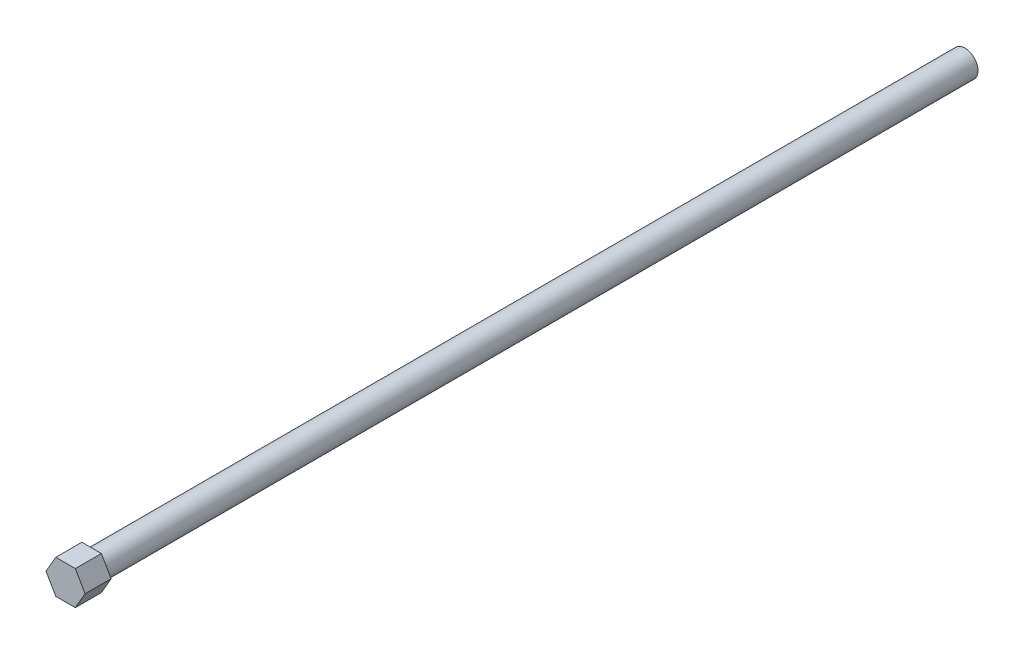
SolidWorks part; units mm, degrees
ref_plane "前视基准面" through (0, 0, 0) normal (0, 0, 1) x (1, 0, 0)
ref_plane "上视基准面" through (0, 0, 0) normal (0, 1, 0) x (1, 0, 0)
ref_plane "右视基准面" through (0, 0, 0) normal (1, 0, 0) x (0, 0, -1)
sketch "草图1" plane through (0, 0, 0) normal (0, 0, 1) x (1, 0, 0)
  circle A0 centre (0, 0) radius 5
  dimension "D1" = 10
extrude "凸台-拉伸1" add sketch "草图1" along normal blind 280
sketch "草图2" plane through (0, 0, 280) normal (0, 0, 1) x (1, 0, 0)
  line L1 (3.75, -6.4952) -> (7.5, 0)
  line L2 (7.5, 0) -> (3.75, 6.4952)
  line L3 (3.75, 6.4952) -> (-3.75, 6.4952)
  line L4 (-3.75, 6.4952) -> (-7.5, 0)
  line L5 (-7.5, 0) -> (-3.75, -6.4952)
  line L6 (-3.75, -6.4952) -> (3.75, -6.4952)
  circle A0 centre (0, 0) radius 7.5 construction
  dimension "D1" = 15
extrude "凸台-拉伸2" add sketch "草图2" along normal blind 10
sketch "草图3" plane through (0, 0, 0) normal (0, 0, -1) x (-1, 0, 0)
  circle A0 centre (0, 0) radius 5
extrude "凸台-拉伸3" add sketch "草图3" along normal blind 55
